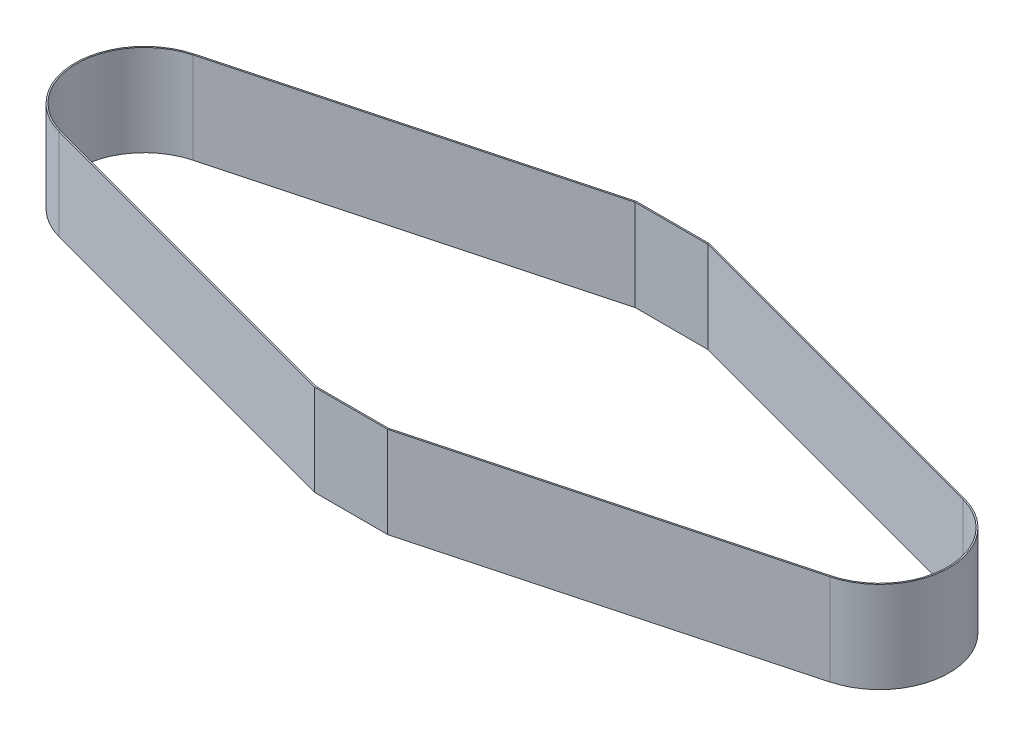
SolidWorks part; units mm, degrees
ref_plane "Front Plane" through (0, 0, 0) normal (0, 0, 1) x (1, 0, 0)
ref_plane "Top Plane" through (0, 0, 0) normal (0, 1, 0) x (1, 0, 0)
ref_plane "Right Plane" through (0, 0, 0) normal (1, 0, 0) x (0, 0, -1)
sketch "Sketch1" plane through (0, 0, 0) normal (0, 1, 0) x (1, 0, 0)
  circle A0 centre (0, 0) radius 77.724
  point P2 (0, 0)
  dimension "D1" = 155.448
extrude "Boss-Extrude1" add sketch "Sketch1" along normal mid plane 101.6
sketch "Sketch2" plane through (0, 0, 0) normal (0, 1, 0) x (1, 0, 0)
  line L0 (-20.1165, -75.0756) -> (368.9438, -179.324)
  line L1 (368.9438, -179.324) -> (450.2062, -179.324)
  line L2 (450.2062, -179.324) -> (839.2665, -75.0756)
  line L3 (839.2665, -75.0756) -> (839.2665, 75.0756)
  line L4 (839.2665, 75.0756) -> (450.2062, 179.324)
  line L5 (450.2062, 179.324) -> (368.9438, 179.324)
  line L6 (368.9438, 179.324) -> (-20.1165, 75.0756)
  line L7 (-20.1165, 75.0756) -> (-20.1165, -75.0756)
  point P8 (0, 0)
  dimension "D1" = 389.0603
  dimension "D2" = 470.3226
  dimension "D3" = 859.3829
  dimension "D4" = 104.2484
  dimension "D5" = 254.3996
  dimension "D6" = 358.648
  dimension "D7" = 839.2665
  dimension "D8" = 179.324
extrude "Boss-Extrude2" add sketch "Sketch2" along normal blind 101.6 from offset 50.8
sketch "Sketch3" plane through (0, 0, 0) normal (0, 1, 0) x (1, 0, 0)
  circle A0 centre (819.15, 0) radius 77.724
  point P2 (0, 0)
  dimension "D1" = 155.448
  dimension "D2" = 819.15
extrude "Boss-Extrude3" add sketch "Sketch3" along normal blind 101.6 from offset 50.8
sketch "Sketch4" plane through (0, 0, 0) normal (0, 1, 0) x (1, 0, 0)
  line L0 (-19.722, -73.6035) -> (369.1444, -177.8)
  line L1 (369.1444, -177.8) -> (450.0056, -177.8)
  line L2 (450.0056, -177.8) -> (838.872, -73.6035)
  line L3 (838.872, -73.6035) -> (838.872, 73.6035)
  line L4 (838.872, 73.6035) -> (450.0056, 177.8)
  line L5 (450.0056, 177.8) -> (369.1444, 177.8)
  line L6 (369.1444, 177.8) -> (-19.722, 73.6035)
  line L7 (-19.722, 73.6035) -> (-19.722, -73.6035)
  point P8 (0, 0)
  dimension "D1" = 388.8665
  dimension "D2" = 469.7276
  dimension "D3" = 858.594
  dimension "D4" = 104.1965
  dimension "D5" = 251.4035
  dimension "D6" = 355.6
  dimension "D7" = 838.872
  dimension "D8" = 177.8
extrude "Cut-Extrude2" cut sketch "Sketch4" along normal through all from offset 50.8
sketch "Sketch5" plane through (0, 0, 0) normal (0, 1, 0) x (1, 0, 0)
  circle A0 centre (0, 0) radius 76.2
  point P2 (0, 0)
  dimension "D1" = 152.4
extrude "Cut-Extrude4" cut sketch "Sketch5" along normal through all from offset 50.8
sketch "Sketch6" plane through (0, 0, 0) normal (0, 1, 0) x (1, 0, 0)
  circle A0 centre (819.15, 0) radius 76.2
  point P2 (0, 0)
  dimension "D1" = 152.4
  dimension "D2" = 819.15
extrude "Cut-Extrude6" cut sketch "Sketch6" along normal through all from offset 50.8
